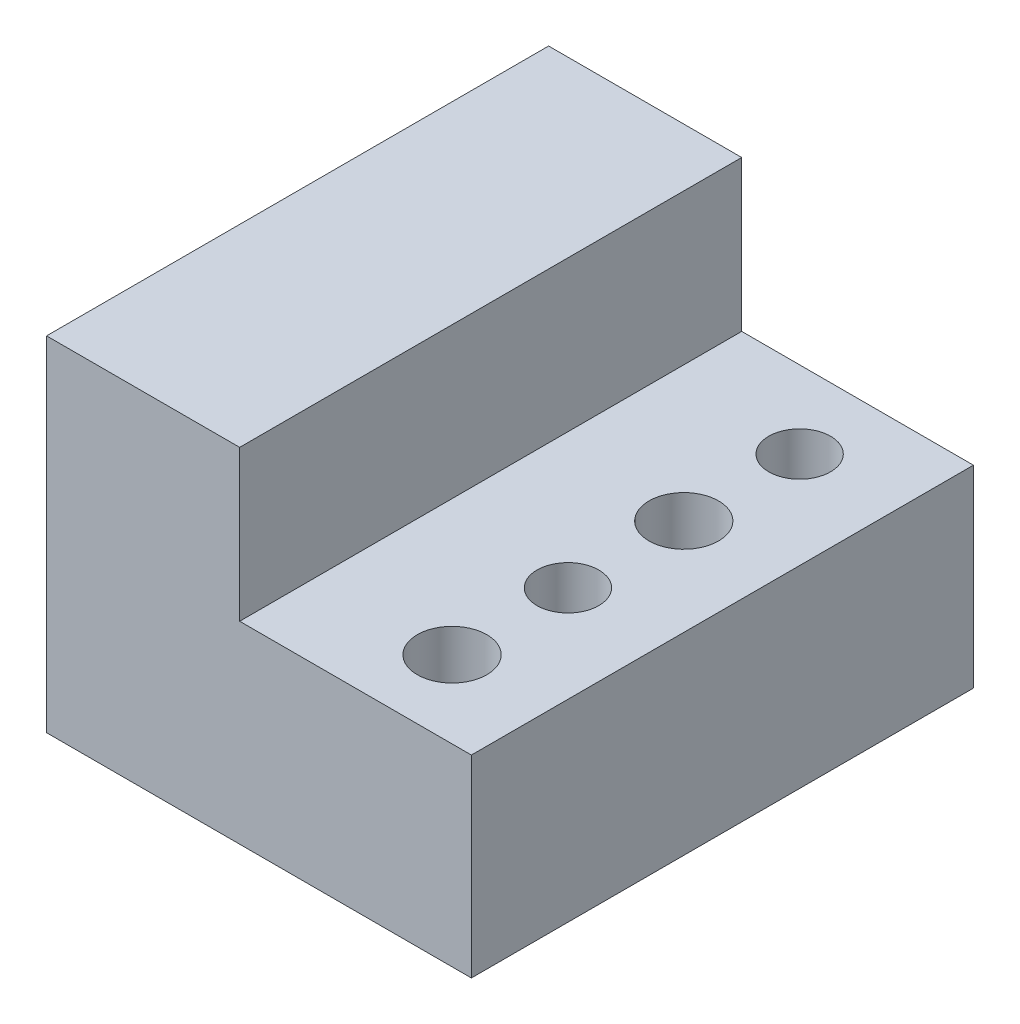
SolidWorks part; units mm, degrees
ref_plane "前视基准面" through (0, 0, 0) normal (0, 0, 1) x (1, 0, 0)
ref_plane "上视基准面" through (0, 0, 0) normal (0, 1, 0) x (1, 0, 0)
ref_plane "右视基准面" through (0, 0, 0) normal (1, 0, 0) x (0, 0, -1)
sketch "草图1" plane through (0, 0, 0) normal (0, 0, 1) x (1, 0, 0)
  line L0 (-30, 44.5) -> (-30, 25)
  line L1 (-30, 25) -> (0, 25)
  line L2 (0, 25) -> (0, 0)
  line L3 (0, 0) -> (-55, 0)
  line L4 (-55, 0) -> (-55, 44.5)
  line L5 (-55, 44.5) -> (-30, 44.5)
  dimension "D1" = 44.5
  dimension "D2" = 55
  dimension "D3" = 25
  dimension "D4" = 25
extrude "凸台-拉伸1" add sketch "草图1" along normal blind 65
hole_wizard "大小mm 暗销孔1" positions "草图3" profile "草图4" hole size "Ø8.0" standard "GB" end condition up to next
sketch "草图3" plane through (0, 25, 0) normal (0, 1, 0) x (1, 0, 0)
  line L1 (0, -65) -> (-30, -65) construction
  line L2 (-55, -65) -> (-55, 0) construction
  point P0 (-12.5, -10)
  point P2 (-12.5, -40)
  dimension "D1" = 55
  dimension "D2" = 42.5
  dimension "D3" = 30
sketch "草图4" plane through (-12.5, 25, 10) normal (1, 0, 0) x (0, 0, 1)
  line L0 (0, 0) -> (0, 25)
  line L1 (0, 25) -> (4, 25)
  line L2 (4, 25) -> (4, 0)
  line L5 (4, 0) -> (0, 0)
  line L11 (0, -6.35) -> (0, 107.95) construction
  dimension "通孔孔直径" = 8
  dimension "通孔孔深度" = 25
sketch "草图5" plane through (0, 25, 0) normal (0, 1, 0) x (1, 0, 0)
  line L0 (-12.5, -10) -> (-12.5, -100) construction
  circle A0 centre (-12.5, -25) radius 4.5
  circle A1 centre (-12.5, -40) radius 4 construction
  circle A3 centre (-12.5, -55) radius 4.5
  dimension "D1" = 9
  dimension "D3" = 9
  dimension "D2" = 15
  dimension "D4" = 15
extrude "切除-拉伸1" cut sketch "草图5" against normal through all
sketch "草图6" plane through (0, 0, 0) normal (0, -1, 0) x (1, 0, 0)
  circle A0 centre (-12.5, 55) radius 7.5
  circle A1 centre (-12.5, 25) radius 7.5
  dimension "D1" = 15
  dimension "D2" = 15
extrude "切除-拉伸2" cut sketch "草图6" against normal blind 10
sketch "草图7" plane through (-55, 0, 0) normal (-1, 0, 0) x (0, 0, 1)
  line L0 (65, 25) -> (0, 25) construction
  line L3 (6, 25) -> (14, 25) construction
  line L4 (20.5, 25) -> (29.5, 25) construction
  line L5 (36, 25) -> (44, 25) construction
  line L6 (50.5, 25) -> (59.5, 25) construction
  circle A0 centre (10, 32) radius 3.4
  circle A1 centre (25, 32) radius 4
  circle A2 centre (40, 32) radius 3.4
  circle A3 centre (55, 32) radius 4
  point P27 (10, 25)
  point P29 (25, 25)
  point P30 (40, 25)
  point P32 (55, 25)
  dimension "D1" = 6.8
  dimension "D2" = 6.8
  dimension "D3" = 8
  dimension "D4" = 8
  dimension "D5" = 7
extrude "切除-拉伸3" cut sketch "草图7" against normal blind 24
